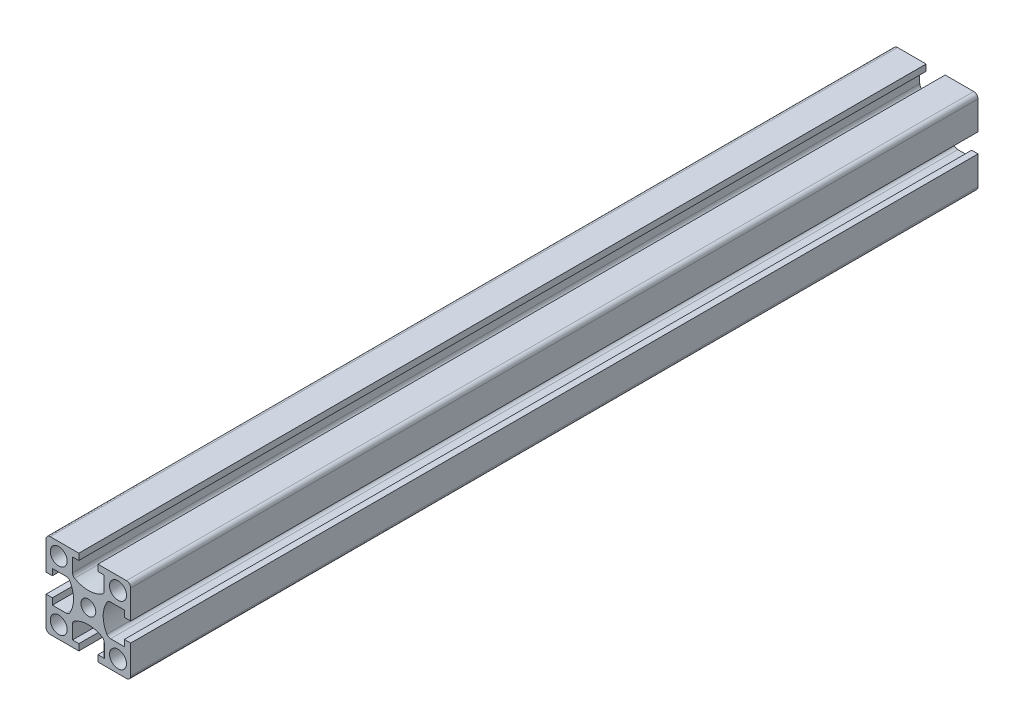
SolidWorks part; units mm, degrees
ref_plane "Front Plane" through (0, 0, 0) normal (0, 0, 1) x (1, 0, 0)
ref_plane "Top Plane" through (0, 0, 0) normal (0, 1, 0) x (1, 0, 0)
ref_plane "Right Plane" through (0, 0, 0) normal (1, 0, 0) x (0, 0, -1)
sketch "Sketch1" plane through (0, 0, 0) normal (0, 0, 1) x (1, 0, 0)
  line L64 (-12.5, 11.25) -> (-12.5, 2.8125)
  line L65 (-12.5, 2.8125) -> (-10.625, 2.8125)
  line L66 (-10.625, 2.8125) -> (-10.625, 4.6875)
  line L67 (-10.625, 4.6875) -> (-6.5461, 4.6875)
  line L68 (-6.5461, -4.6875) -> (-10.625, -4.6875)
  line L69 (-10.625, -4.6875) -> (-10.625, -2.8125)
  line L70 (-10.625, -2.8125) -> (-12.5, -2.8125)
  line L71 (-12.5, -2.8125) -> (-12.5, -11.25)
  line L72 (-11.25, -12.5) -> (-2.8125, -12.5)
  line L73 (-2.8125, -12.5) -> (-2.8125, -10.625)
  line L74 (-2.8125, -10.625) -> (-4.6875, -10.625)
  line L75 (-4.6875, -10.625) -> (-4.6875, -6.5461)
  line L76 (4.6875, -6.5461) -> (4.6875, -10.625)
  line L77 (4.6875, -10.625) -> (2.8125, -10.625)
  line L78 (2.8125, -10.625) -> (2.8125, -12.5)
  line L79 (2.8125, -12.5) -> (11.25, -12.5)
  line L80 (12.5, -11.25) -> (12.5, -2.8125)
  line L81 (12.5, -2.8125) -> (10.625, -2.8125)
  line L82 (10.625, -2.8125) -> (10.625, -4.6875)
  line L83 (10.625, -4.6875) -> (6.5461, -4.6875)
  line L84 (6.5461, 4.6875) -> (10.625, 4.6875)
  line L85 (10.625, 4.6875) -> (10.625, 2.8125)
  line L86 (10.625, 2.8125) -> (12.5, 2.8125)
  line L87 (12.5, 2.8125) -> (12.5, 11.25)
  line L88 (11.25, 12.5) -> (2.8125, 12.5)
  line L89 (2.8125, 12.5) -> (2.8125, 10.625)
  line L90 (2.8125, 10.625) -> (4.6875, 10.625)
  line L91 (4.6875, 10.625) -> (4.6875, 6.5461)
  line L92 (-4.6875, 6.5461) -> (-4.6875, 10.625)
  line L93 (-4.6875, 10.625) -> (-2.8125, 10.625)
  line L94 (-2.8125, 10.625) -> (-2.8125, 12.5)
  line L95 (-2.8125, 12.5) -> (-11.25, 12.5)
  circle A5 centre (-8.75, -8.75) radius 2.5
  circle A6 centre (8.75, -8.75) radius 2.5
  circle A7 centre (8.75, 8.75) radius 2.5
  circle A8 centre (0, 0) radius 2.1875
  circle A9 centre (-8.75, 8.75) radius 2.5
  arc A32 (-11.25, 12.5) -> (-12.5, 11.25) centre (-11.25, 11.25) ccw
  arc A33 (-5.4635, 4.0625) -> (-6.5461, 4.6875) centre (-6.5461, 3.4375) ccw
  arc A34 (-5.4635, -4.0625) -> (-5.4635, 4.0625) centre (-12.5, 0) ccw
  arc A35 (-6.5461, -4.6875) -> (-5.4635, -4.0625) centre (-6.5461, -3.4375) ccw
  arc A36 (-12.5, -11.25) -> (-11.25, -12.5) centre (-11.25, -11.25) ccw
  arc A37 (-4.0625, -5.4635) -> (-4.6875, -6.5461) centre (-3.4375, -6.5461) ccw
  arc A38 (4.0625, -5.4635) -> (-4.0625, -5.4635) centre (0, -12.5) ccw
  arc A39 (4.6875, -6.5461) -> (4.0625, -5.4635) centre (3.4375, -6.5461) ccw
  arc A40 (11.25, -12.5) -> (12.5, -11.25) centre (11.25, -11.25) ccw
  arc A41 (5.4635, -4.0625) -> (6.5461, -4.6875) centre (6.5461, -3.4375) ccw
  arc A42 (5.4635, 4.0625) -> (5.4635, -4.0625) centre (12.5, 0) ccw
  arc A43 (6.5461, 4.6875) -> (5.4635, 4.0625) centre (6.5461, 3.4375) ccw
  arc A44 (12.5, 11.25) -> (11.25, 12.5) centre (11.25, 11.25) ccw
  arc A45 (4.0625, 5.4635) -> (4.6875, 6.5461) centre (3.4375, 6.5461) ccw
  arc A46 (-4.0625, 5.4635) -> (4.0625, 5.4635) centre (0, 12.5) ccw
  arc A47 (-4.6875, 6.5461) -> (-4.0625, 5.4635) centre (-3.4375, 6.5461) ccw
extrude "Boss-Extrude1" add sketch "Sketch1" along normal blind 250
